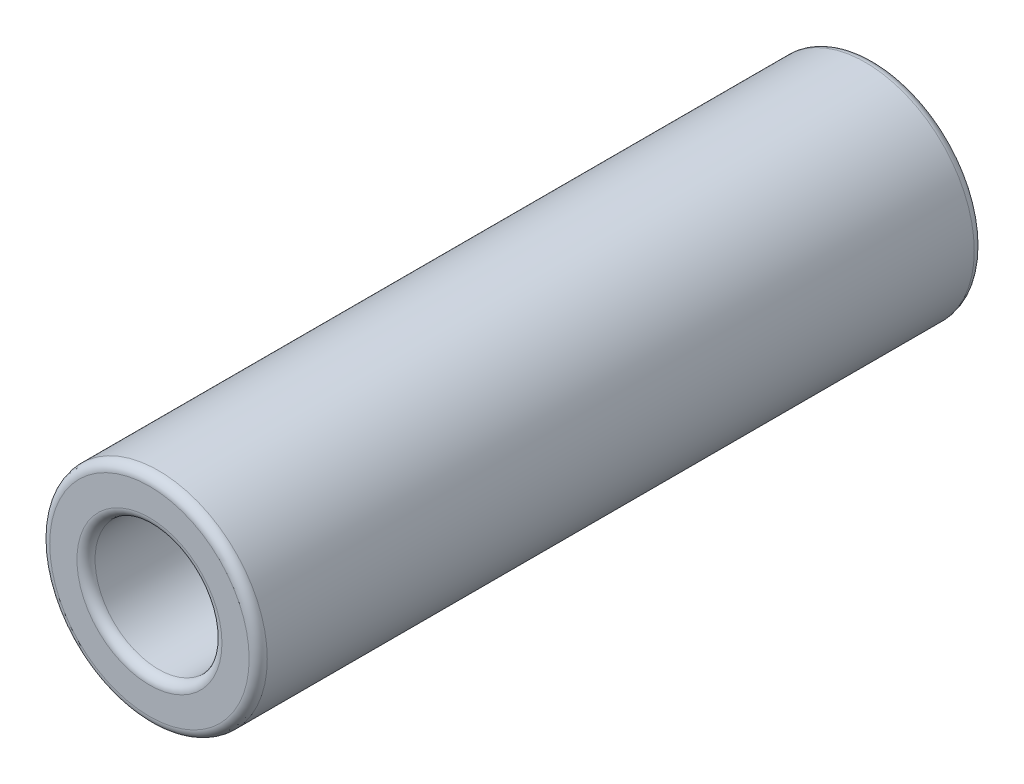
SolidWorks part; units mm, degrees
ref_plane "Płaszczyzna przednia" through (0, 0, 0) normal (0, 0, 1) x (1, 0, 0)
ref_plane "Płaszczyzna górna" through (0, 0, 0) normal (0, 1, 0) x (1, 0, 0)
ref_plane "Płaszczyzna prawa" through (0, 0, 0) normal (1, 0, 0) x (0, 0, -1)
sketch "Szkic1" plane through (0, 0, 0) normal (0, 0, 1) x (1, 0, 0)
  circle A0 centre (0, 0) radius 3.5
  circle A1 centre (0, 0) radius 6
  dimension "D1" = 7
  dimension "D2" = 12
extrude "Dodanie-wyciągnięcie1" add sketch "Szkic1" along normal blind 40 contours A0 | A1
fillet "Zaokrąglenie1" radius 0.5 2 edges at (3.5, 0, 0) (6, 0, 0)
fillet "Zaokrąglenie2" radius 0.5 2 edges at (3.5, 0, 40) (6, 0, 40)
